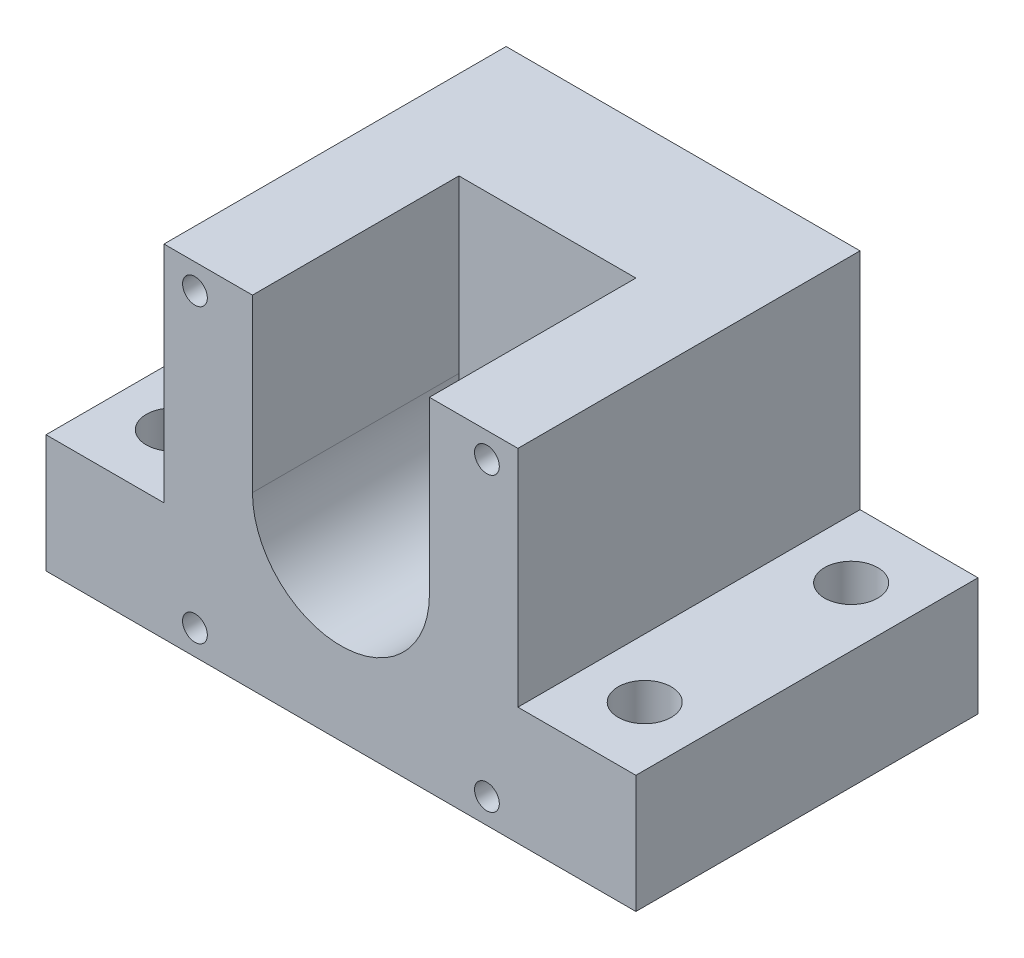
SolidWorks part; units mm, degrees
ref_plane "Front Plane" through (0, 0, 0) normal (0, 0, 1) x (1, 0, 0)
ref_plane "Top Plane" through (0, 0, 0) normal (0, 1, 0) x (1, 0, 0)
ref_plane "Right Plane" through (0, 0, 0) normal (1, 0, 0) x (0, 0, -1)
sketch "Sketch2" plane through (0, 0, 0) normal (0, 1, 0) x (1, 0, 0)
  line L0 (-50, 0) -> (0, 0)
  line L1 (50, 0) -> (50, 58)
  line L2 (50, 58) -> (-50, 58)
  line L3 (-50, 58) -> (-50, 0)
  line L4 (0, 0) -> (50, 0)
  dimension "D1" = 58
  dimension "D2" = 100
extrude "Boss-Extrude1" add sketch "Sketch2" along normal blind 58
sketch "Sketch3" plane through (0, 0, -58) normal (0, 0, 1) x (1, 0, 0)
  line L0 (0, 58) -> (0, 0) construction
  line L1 (-50, 58) -> (50, 58) construction
  line L2 (-50, 29) -> (50, 29) construction
  line L3 (-50, 58) -> (-50, 0) construction
  line L4 (50, 58) -> (50, 0) construction
  circle A0 centre (0, 29) radius 11
  point P11 (0, 29)
  dimension "D1" = 22
extrude "Cut-Extrude1" cut sketch "Sketch3" along normal blind 13
sketch "Sketch4" plane through (0, 0, -45) normal (0, 0, -1) x (-1, 0, 0)
  circle A0 centre (0, 29) radius 8
  dimension "D1" = 16
extrude "Cut-Extrude2" cut sketch "Sketch4" against normal through all
sketch "Sketch5" plane through (0, 0, 0) normal (0, 0, 1) x (1, 0, 0)
  line L0 (-50, 29) -> (50, 29) construction
  circle A0 centre (0, 29) radius 15
  dimension "D1" = 30
extrude "Cut-Extrude3" cut sketch "Sketch5" against normal offset from surface (35 mm away) 10 up to face at (-8, 29, -45)
sketch "Sketch6" plane through (0, 0, 0) normal (0, 0, 1) x (1, 0, 0)
  line L1 (-15, 29) -> (-15, 58)
  line L2 (-50, 29) -> (50, 29) construction
  line L3 (-50, 58) -> (50, 58) construction
  line L4 (-15, 58) -> (15, 58)
  line L5 (15, 58) -> (15, 29)
  line L6 (-15, 29) -> (15, 29)
  circle A0 centre (0, 29) radius 15 construction
extrude "Cut-Extrude4" cut sketch "Sketch6" against normal up to surface (35 mm away) up to face at (15, 29, -35)
hole_wizard "M5 Tapped Hole1" positions "Sketch9" profile "Sketch10" tap size "M5" standard "ISO" end condition through all
sketch "Sketch9" plane through (8.7044, 17.3949, 0) normal (0, 0, 1) x (1, 0, 0)
  point P4 (16.0443, 36.3538)
  point P7 (-33.4532, 36.3538)
  point P10 (-33.4532, -13.1436)
  point P13 (16.0443, -13.1436)
sketch "Sketch10" plane through (24.7487, 53.7487, 0) normal (1, 0, 0) x (0, -1, 0)
  line L0 (0, 0) -> (0, 58)
  line L1 (0, 58) -> (2.1, 58)
  line L2 (2.1, 58) -> (2.1, 0)
  line L3 (2.1, 0) -> (0, 0)
  line L4 (0, -6.35) -> (0, 107.95) construction
  dimension "Thread Major Dia." = 4.2
  dimension "Thru Tap Drill Depth" = 58
sketch "Sketch12" plane through (0, 58, 0) normal (0, 1, 0) x (1, 0, 0)
  line L0 (-50, 0) -> (-15, 0) construction
  line L1 (-50, 58) -> (-30, 58)
  line L2 (-50, 58) -> (-50, 0)
  line L3 (-50, 0) -> (-30, 0)
  line L4 (-30, 58) -> (-30, 0)
  line L5 (0, 58) -> (0, 0) construction
  line L6 (-50, 58) -> (50, 58) construction
  line L7 (30, 58) -> (30, 0)
  line L8 (50, 0) -> (30, 0)
  line L9 (50, 58) -> (50, 0)
  line L10 (50, 58) -> (30, 58)
  line L11 (-40, 58) -> (-40, 35) construction
  line L12 (-50, 35) -> (-15, 35) construction
  line L13 (-15, 35) -> (15, 35) construction
  line L14 (15, 35) -> (50, 35) construction
  line L16 (-50, 29) -> (-30, 29) construction
  point P24 (-40, 35)
  point P26 (-40, 46.5)
  point P28 (-40, 11.5)
  point P29 (40, 11.5)
  point P30 (40, 46.5)
  dimension "D1" = 60
extrude "Cut-Extrude6" cut sketch "Sketch12" against normal offset from surface (38 mm away) 20 up to face at (0, 0, -29)
hole_wizard "M8 Clearance Hole1" positions "Sketch13" profile "Sketch14" hole size "M8" standard "ISO"
sketch "Sketch13" plane through (8.7044, 20, -505.3361) normal (0, 1, 0) x (1, 0, 0)
  point P0 (-48.7044, -458.8361)
  point P3 (-48.7044, -493.8361)
  point P6 (31.2956, -458.8361)
  point P9 (31.2956, -493.8361)
  point P12 (-48.7044, 58.0784)
  point P15 (31.2956, 58.0784)
sketch "Sketch14" plane through (-40, 20, -46.5) normal (1, 0, 0) x (0, 0, 1)
  line L0 (0, 0) -> (0, 22.7029)
  line L1 (0, 22.7029) -> (4.5, 19.999)
  line L2 (4.5, 19.999) -> (4.5, 0)
  line L3 (4.5, 0) -> (0, 0)
  line L4 (0, 22.7029) -> (-4.5, 19.999) construction
  line L5 (0, -6.35) -> (0, 107.95) construction
  dimension "Hole Dia." = 9
  dimension "Hole Depth" = 19.999
  dimension "Drill Angle" = 118
